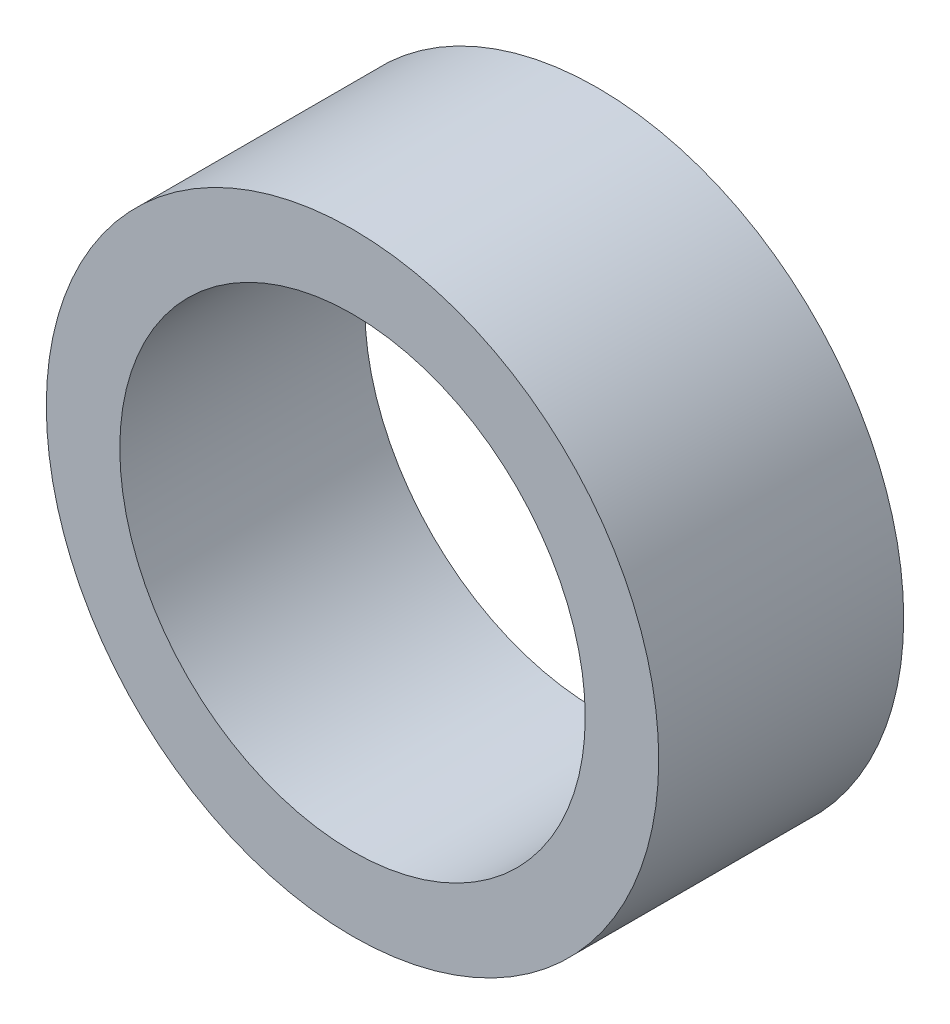
SolidWorks part; units mm, degrees
ref_plane "Front Plane" through (0, 0, 0) normal (0, 0, 1) x (1, 0, 0)
ref_plane "Top Plane" through (0, 0, 0) normal (0, 1, 0) x (1, 0, 0)
ref_plane "Right Plane" through (0, 0, 0) normal (1, 0, 0) x (0, 0, -1)
sketch "Sketch1" plane through (0, 0, 0) normal (0, 0, 1) x (1, 0, 0)
  circle A0 centre (0, 0) radius 7.6
  circle A1 centre (0, 0) radius 10
  dimension "D1" = 15.2
  dimension "D2" = 20
extrude "Boss-Extrude1" add sketch "Sketch1" along normal mid plane 8
